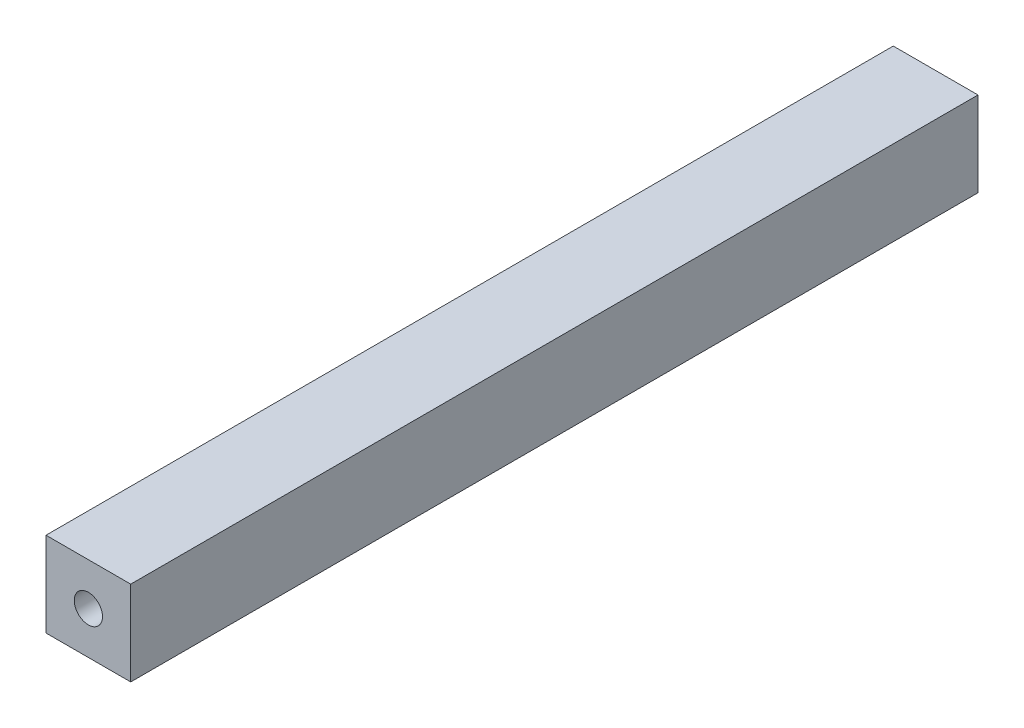
SolidWorks part; units mm, degrees
ref_plane "Front" through (0, 0, 0) normal (0, 0, 1) x (1, 0, 0)
ref_plane "Top" through (0, 0, 0) normal (0, 1, 0) x (1, 0, 0)
ref_plane "Right" through (0, 0, 0) normal (1, 0, 0) x (0, 0, -1)
sketch "Sketch1" plane through (0, 0, 0) normal (0, 0, 1) x (1, 0, 0)
  line L0 (-4.5, 4.5) -> (4.5, 4.5)
  line L1 (-1.5, -1.5) -> (1.5, -1.5)
  line L2 (-1.5, -1.5) -> (-1.5, 1.5)
  line L3 (-1.5, 1.5) -> (1.5, 1.5)
  line L4 (1.5, -1.5) -> (1.5, 1.5)
  line L5 (4.5, -4.5) -> (4.5, 4.5)
  line L6 (-4.5, -4.5) -> (4.5, -4.5)
  line L7 (-4.5, -4.5) -> (-4.5, 4.5)
  circle A0 centre (0, 0) radius 1.5
  dimension "D1" = 3
  dimension "D2" = 3
extrude "Boss-Extrude1" add sketch "Sketch1" along normal blind 90 contours L7 L6 L5 L0 L4 L1 L2 L3 | A0 L3 L2 | A0 L4 L3 | A0 L1 L4 | A0 L2 L1
